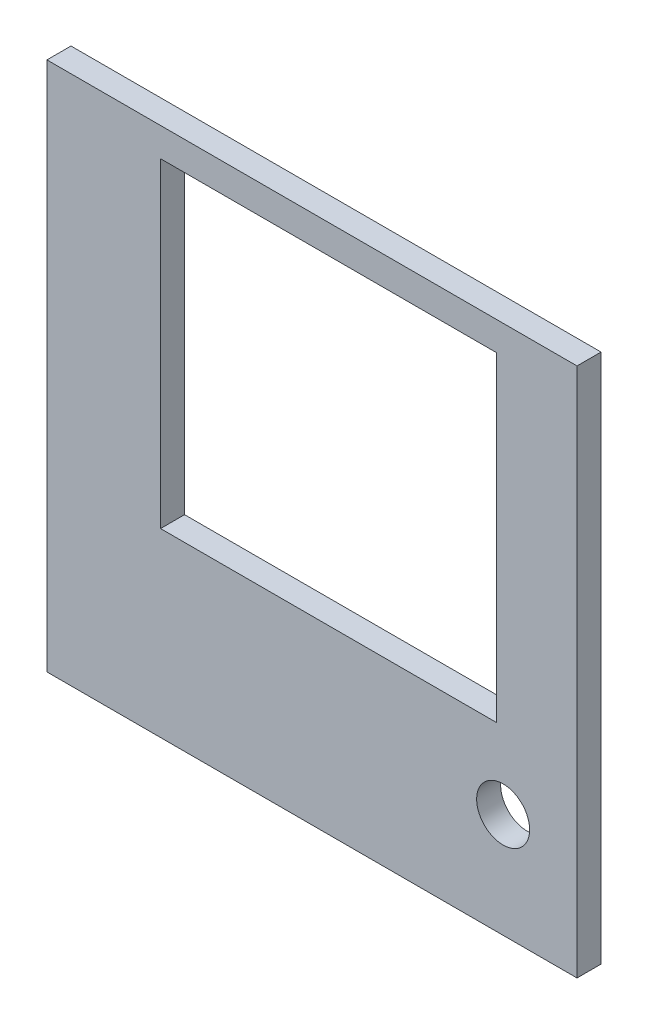
SolidWorks part; units mm, degrees
ref_plane "Front Plane" through (0, 0, 0) normal (0, 0, 1) x (1, 0, 0)
ref_plane "Top Plane" through (0, 0, 0) normal (0, 1, 0) x (1, 0, 0)
ref_plane "Right Plane" through (0, 0, 0) normal (1, 0, 0) x (0, 0, -1)
sketch "Sketch1" plane through (0, 0, 0) normal (0, 0, 1) x (1, 0, 0)
  line L1 (0, 0) -> (70, 0)
  line L2 (0, 0) -> (0, 70)
  line L3 (0, 70) -> (70, 70)
  line L4 (70, 0) -> (70, 70)
  line L5 (59.35, 66.2) -> (15, 66.2)
  line L6 (59.35, 66.2) -> (59.35, 23.9)
  line L7 (59.35, 23.9) -> (15, 23.9)
  line L8 (15, 66.2) -> (15, 23.9)
  circle A0 centre (60.245, 13.825) radius 3.5
  dimension "D7" = 7
  dimension "D1" = 70
  dimension "D2" = 70
  dimension "D3" = 42.3
  dimension "D4" = 44.35
  dimension "D5" = 3.8
  dimension "D6" = 15
extrude "Boss-Extrude1" add sketch "Sketch1" along normal blind 3.175
